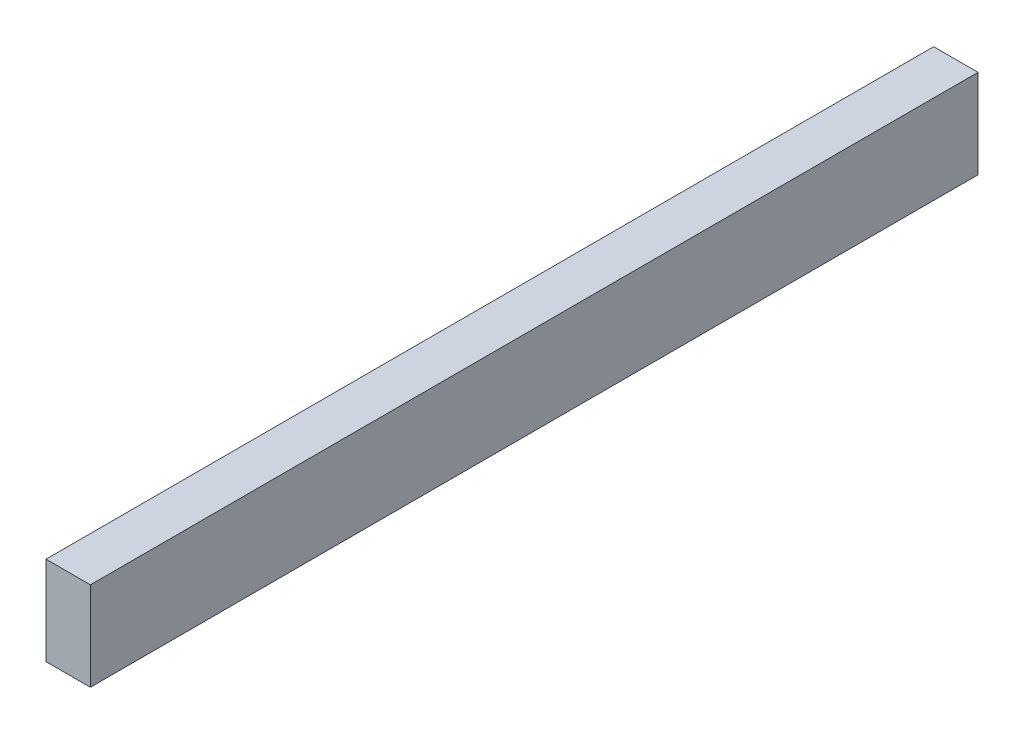
SolidWorks part; units mm, degrees
material "Balsa"
ref_plane "Ebene vorne" through (0, 0, 0) normal (0, 0, 1) x (1, 0, 0)
ref_plane "Ebene oben" through (0, 0, 0) normal (0, 1, 0) x (1, 0, 0)
ref_plane "Ebene rechts" through (0, 0, 0) normal (1, 0, 0) x (0, 0, -1)
sketch "Skizze1" plane through (0, 0, 0) normal (0, 0, 1) x (1, 0, 0)
  line L1 (-1.9739, 0.5025) -> (-0.4739, 0.5025)
  line L2 (-1.9739, 0.5025) -> (-1.9739, -2.4975)
  line L3 (-1.9739, -2.4975) -> (-0.4739, -2.4975)
  line L4 (-0.4739, 0.5025) -> (-0.4739, -2.4975)
  dimension "D1" = 1.5
  dimension "D2" = 3
extrude "Aufsatz-Linear austragen1" add sketch "Skizze1" along normal blind 30
